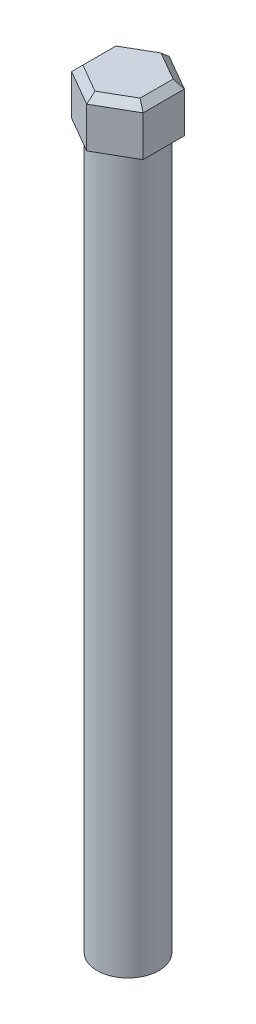
SolidWorks part; units mm, degrees
ref_plane "Front Plane" through (0, 0, 0) normal (0, 0, 1) x (1, 0, 0)
ref_plane "Top Plane" through (0, 0, 0) normal (0, 1, 0) x (1, 0, 0)
ref_plane "Right Plane" through (0, 0, 0) normal (1, 0, 0) x (0, 0, -1)
sketch "Sketch1" plane through (0, 0, 0) normal (0, 0, 1) x (1, 0, 0)
  line L0 (0, 0) -> (0, 3)
  line L1 (0, 3) -> (0.13, 3)
  line L2 (0.13, 3) -> (0.13, 0)
  line L3 (0.13, 0) -> (0, 0)
  dimension "D1" = 0.13
  dimension "D2" = 3
revolve "Revolve2" add sketch "Sketch1" angle 360 about L0
sketch "Sketch3" plane through (0, 3, 0) normal (0, 1, 0) x (1, 0, 0)
  line L1 (0, 0.1732) -> (-0.15, 0.0866)
  line L2 (-0.15, 0.0866) -> (-0.15, -0.0866)
  line L3 (-0.15, -0.0866) -> (0, -0.1732)
  line L4 (0, -0.1732) -> (0.15, -0.0866)
  line L5 (0.15, -0.0866) -> (0.15, 0.0866)
  line L6 (0.15, 0.0866) -> (0, 0.1732)
  circle A0 centre (0, 0) radius 0.15 construction
  dimension "D1" = 0.3
extrude "Boss-Extrude1" add sketch "Sketch3" along normal blind 0.2
chamfer "Chamfer5" distance 0.03 angle 45 6 edges at (0.15, 3.2, 0) (0.075, 3.2, -0.1299) (-0.075, 3.2, -0.1299) (-0.15, 3.2, 0) (-0.075, 3.2, 0.1299) (0.075, 3.2, 0.1299)
